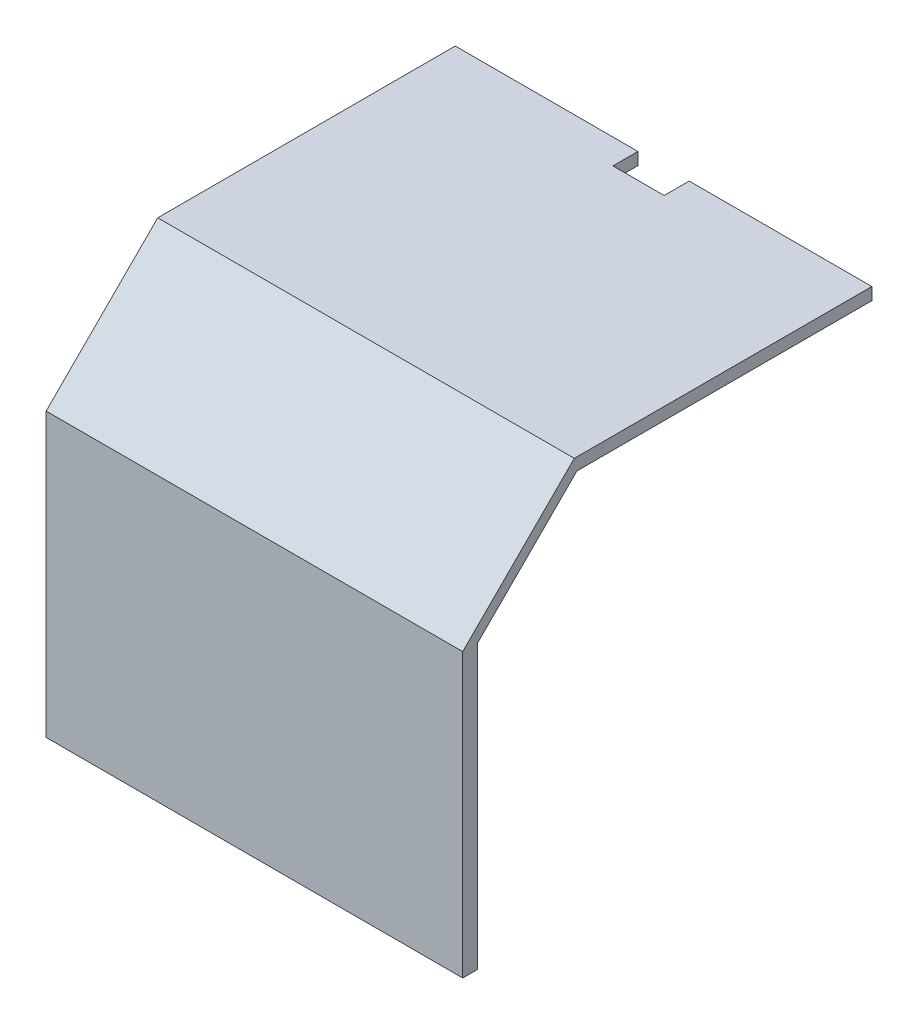
SolidWorks part; units mm, degrees
ref_plane "Front Plane" through (0, 0, 0) normal (0, 0, 1) x (1, 0, 0)
ref_plane "Top Plane" through (0, 0, 0) normal (0, 1, 0) x (1, 0, 0)
ref_plane "Right Plane" through (0, 0, 0) normal (1, 0, 0) x (0, 0, -1)
sketch "Sketch1" plane through (0, 0, 0) normal (0, 1, 0) x (1, 0, 0)
  line L1 (-560, -20) -> (560, -20)
  line L2 (-560, -20) -> (-560, 20)
  line L3 (-560, 20) -> (560, 20)
  line L4 (560, -20) -> (560, 20)
  line L5 (-560, -20) -> (560, 20) construction
  line L6 (-560, 20) -> (560, -20) construction
  point P0 (0, 0)
  dimension "D1" = 40
  dimension "D2" = 1120
extrude "Boss-Extrude1" add sketch "Sketch1" along normal blind 760
sketch "Sketch2" plane through (560, 0, 0) normal (1, 0, 0) x (0, 0, -1)
  line L0 (-20, 760) -> (280, 1060)
  line L1 (-20, 760) -> (20, 760)
  line L2 (20, 760) -> (320, 1060)
  line L3 (320, 1060) -> (280, 1060)
  line L4 (-20, 760) -> (20, 760) construction
  point P7 (0, 0)
  dimension "D1" = 300
  dimension "D2" = 28.2843
extrude "Boss-Extrude2" add sketch "Sketch2" against normal blind 1120
sketch "Sketch3" plane through (560, 0, 0) normal (1, 0, 0) x (0, 0, -1)
  line L0 (320, 1060) -> (1080, 1060)
  line L1 (1080, 1060) -> (1080, 1027)
  line L2 (1080, 1027) -> (285.5708, 1027)
  line L3 (285.5708, 1027) -> (320, 1060)
  dimension "D1" = 33
  dimension "D2" = 33
  dimension "D3" = 760
  dimension "D4" = 34.4292
extrude "Boss-Extrude3" add sketch "Sketch3" against normal blind 1120
sketch "Sketch4" plane through (0, 1060, 0) normal (0, 1, 0) x (1, 0, 0)
  line L0 (-68.8845, 1012.7621) -> (-68.8845, 1080)
  line L1 (68.8845, 1080) -> (68.8845, 1012.7621)
  line L2 (-68.8845, 1080) -> (68.8845, 1080)
  line L3 (68.8845, 1012.7621) -> (-68.8845, 1012.7621)
  line L4 (-560, 1080) -> (560, 1080) construction
  line L6 (0, 1080) -> (0, 1012.7621) construction
  line L7 (0, 280) -> (0, 1183.1082) construction
  line L8 (-560, 280) -> (560, 280) construction
extrude "Cut-Extrude1" cut sketch "Sketch4" against normal blind 1120
